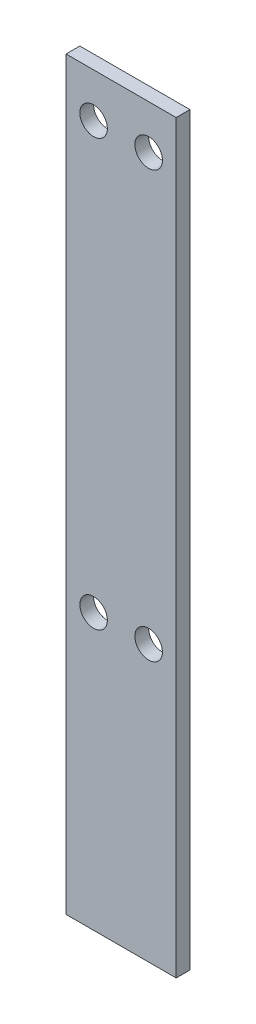
SolidWorks part; units mm, degrees
ref_plane "Front Plane" through (0, 0, 0) normal (0, 0, 1) x (1, 0, 0)
ref_plane "Top Plane" through (0, 0, 0) normal (0, 1, 0) x (1, 0, 0)
ref_plane "Right Plane" through (0, 0, 0) normal (1, 0, 0) x (0, 0, -1)
sketch "Sketch1" plane through (0, 0, 0) normal (0, 0, 1) x (1, 0, 0)
  line L0 (0, 9.9974) -> (38.1, 9.9974) construction
  line L1 (0, 0) -> (38.1, 0)
  line L2 (0, 0) -> (0, 257.81)
  line L3 (0, 257.81) -> (38.1, 257.81)
  line L4 (38.1, 0) -> (38.1, 257.81)
  line L5 (19.05, 95.25) -> (38.1, 95.25) construction
  line L6 (19.05, 225.3621) -> (38.1, 225.3621) construction
  circle A0 centre (9.525, 95.25) radius 4.7625
  circle A1 centre (28.575, 95.25) radius 4.7625
  circle A2 centre (9.525, 242.57) radius 4.7625
  circle A3 centre (28.575, 242.57) radius 4.7625
  point P13 (19.05, 9.9974)
  point P14 (28.575, 95.25)
  point P21 (19.05, 257.81)
  point P22 (28.575, 225.3621)
  dimension "D4" = 9.525
  dimension "D6" = 9.525
  dimension "10" = 257.81
  dimension "D2" = 38.1
  dimension "D3" = 19.05
  dimension "D5" = 162.56
  dimension "D7" = 19.05
  dimension "D8" = 15.24
extrude "Boss-Extrude1" add sketch "Sketch1" along normal blind 4.7625
